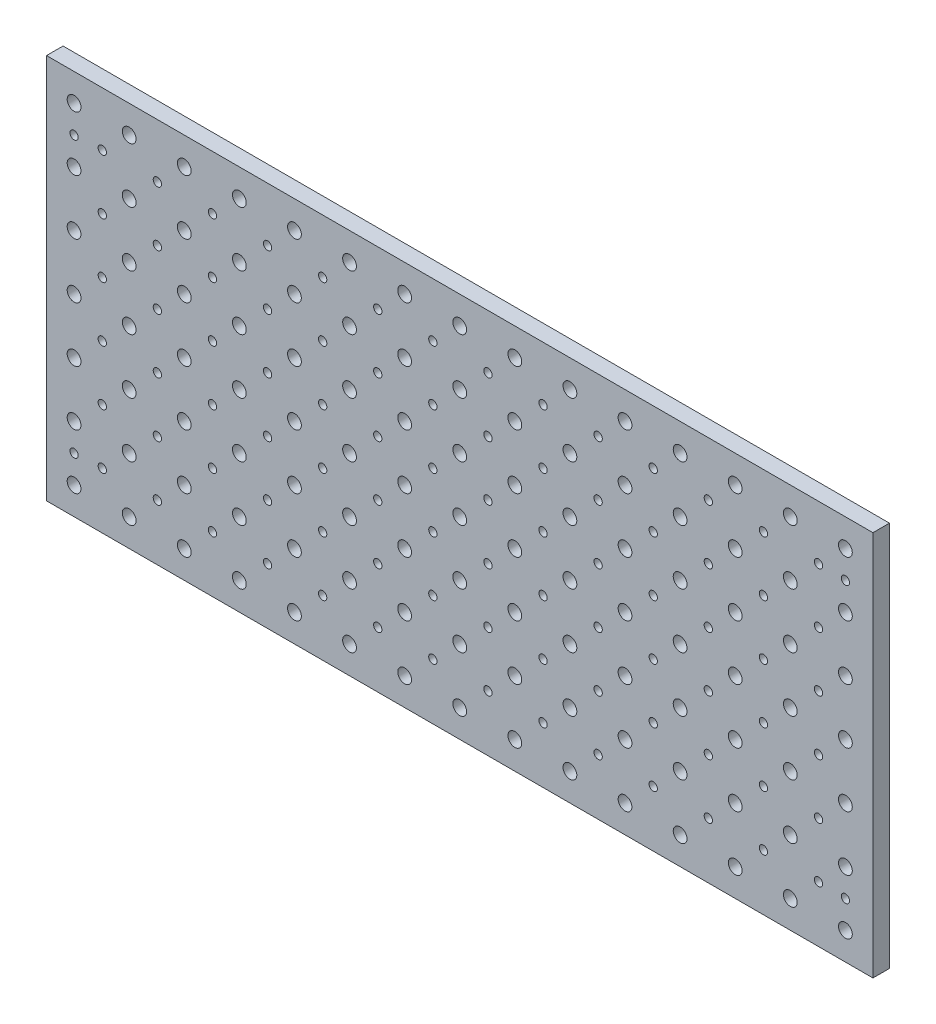
SolidWorks part; units mm, degrees
ref_plane "Ebene vorne" through (0, 0, 0) normal (0, 0, 1) x (1, 0, 0)
ref_plane "Ebene oben" through (0, 0, 0) normal (0, 1, 0) x (1, 0, 0)
ref_plane "Ebene rechts" through (0, 0, 0) normal (1, 0, 0) x (0, 0, -1)
sketch "Skizze1" plane through (0, 0, 0) normal (0, 0, 1) x (1, 0, 0)
  line L1 (-150, 70) -> (150, 70)
  line L2 (-150, 70) -> (-150, -70)
  line L3 (-150, -70) -> (150, -70)
  line L4 (150, 70) -> (150, -70)
  dimension "D1" = 300
  dimension "D2" = 140
  dimension "D3" = 150
  dimension "D4" = 70
extrude "Aufsatz-Linear austragen2" add sketch "Skizze1" along normal blind 6 contours L1 L4 L3 L2
sketch "Skizze2" plane through (0, 0, 0) normal (0, 0, -1) x (-1, 0, 0)
  circle A0 centre (-140, 60) radius 2.5
extrude "Schnitt-Linear austragen1" cut sketch "Skizze2" against normal blind 6
pattern_linear "Lineares Muster1" count 15 spacing 20 along (-1, 0, 0) count 7 spacing 20 along (0, -1, 0) of "Schnitt-Linear austragen1"
sketch "Skizze4" plane through (0, 0, 0) normal (0, 0, -1) x (-1, 0, 0)
  circle A0 centre (-130.2417, 50.3739) radius 1.51
extrude "Schnitt-Linear austragen2" cut sketch "Skizze4" against normal blind 6 contours A0
pattern_linear "Lineares Muster2" count 14 spacing 20 along (-1, 0, 0) count 6 spacing 20 along (0, -1, 0) of "Schnitt-Linear austragen2"
sketch "Skizze5" plane through (0, 0, 0) normal (0, 0, -1) x (-1, 0, 0)
  circle A0 centre (-140, 50) radius 1.5
extrude "Schnitt-Linear austragen3" cut sketch "Skizze5" against normal blind 10
pattern_linear "Lineares Muster3" count 2 spacing 280 along (-1, 0, 0) count 2 spacing 100 along (0, -1, 0) of "Schnitt-Linear austragen3"
